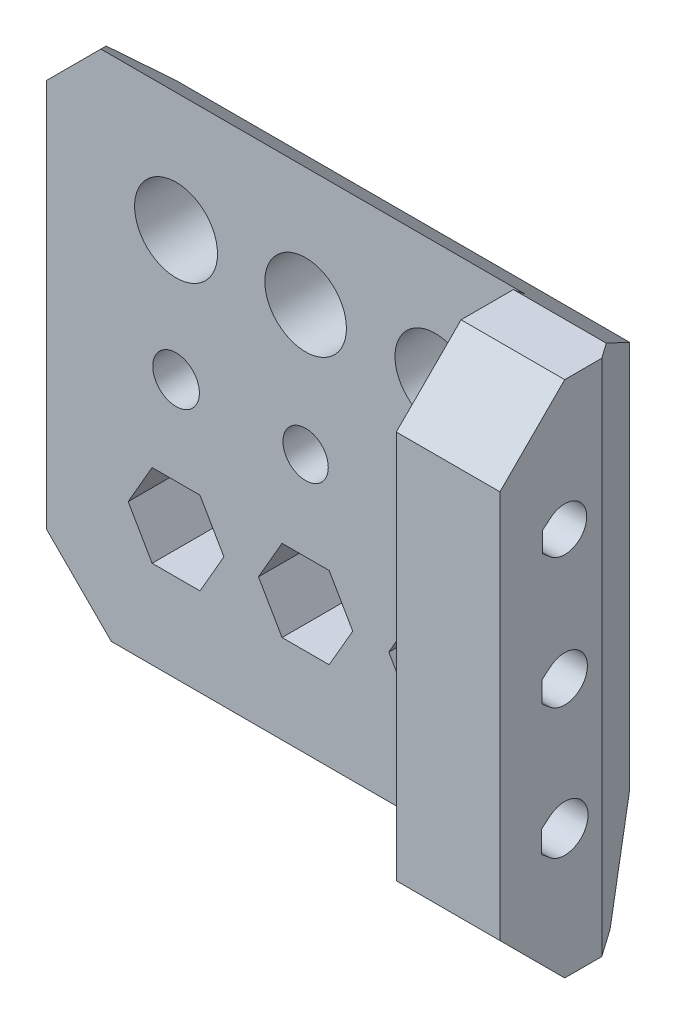
SolidWorks part; units mm, degrees
ref_plane "Front Plane" through (0, 0, 0) normal (0, 0, 1) x (1, 0, 0)
ref_plane "Top Plane" through (0, 0, 0) normal (0, 1, 0) x (1, 0, 0)
ref_plane "Right Plane" through (0, 0, 0) normal (1, 0, 0) x (0, 0, -1)
sketch "Sketch1" plane through (0, 0, 0) normal (0, 0, 1) x (1, 0, 0)
  line L0 (0, 0) -> (-30, 0) construction
  line L1 (-30, -20) -> (15, -20)
  line L2 (-30, -20) -> (-30, 20)
  line L3 (-30, 20) -> (15, 20)
  line L4 (15, -20) -> (15, 20)
  line L5 (-16.305, -10) -> (-18.1525, -6.8)
  line L6 (-18.1525, -6.8) -> (-21.8475, -6.8)
  line L7 (-21.8475, -6.8) -> (-23.695, -10)
  line L8 (-23.695, -10) -> (-21.8475, -13.2)
  line L9 (-21.8475, -13.2) -> (-18.1525, -13.2)
  line L10 (-18.1525, -13.2) -> (-16.305, -10)
  line L11 (-6.3627, -10) -> (-8.1813, -6.85)
  line L12 (-8.1813, -6.85) -> (-11.8187, -6.85)
  line L13 (-11.8187, -6.85) -> (-13.6373, -10)
  line L14 (-13.6373, -10) -> (-11.8187, -13.15)
  line L15 (-11.8187, -13.15) -> (-8.1813, -13.15)
  line L16 (-8.1813, -13.15) -> (-6.3627, -10)
  line L17 (3.5796, -10) -> (1.7898, -6.9)
  line L18 (1.7898, -6.9) -> (-1.7898, -6.9)
  line L19 (-1.7898, -6.9) -> (-3.5796, -10)
  line L20 (-3.5796, -10) -> (-1.7898, -13.1)
  line L21 (-1.7898, -13.1) -> (1.7898, -13.1)
  line L22 (1.7898, -13.1) -> (3.5796, -10)
  circle A0 centre (-20, 0) radius 1.8
  circle A1 centre (-10, 0) radius 1.75
  circle A2 centre (0, 0) radius 1.7
  circle A3 centre (-20, 10) radius 3.2
  circle A4 centre (-10, 10) radius 3.15
  circle A5 centre (0, 10) radius 3.1
  circle A6 centre (-20, -10) radius 3.2 construction
  circle A7 centre (-10, -10) radius 3.15 construction
  circle A8 centre (0, -10) radius 3.1 construction
  dimension "D1" = 6.4
  dimension "D2" = 6.3
  dimension "D3" = 6.2
  dimension "D4" = 3.4
  dimension "D5" = 3.5
  dimension "D6" = 3.6
  dimension "D7" = 6.4
  dimension "D8" = 6.3
  dimension "D9" = 6.2
  dimension "D10" = 10
  dimension "D11" = 10
  dimension "D12" = 10
  dimension "D13" = 10
  dimension "D14" = 10
  dimension "D15" = 15
  dimension "D16" = 10
  dimension "D17" = 10
extrude "Boss-Extrude1" add sketch "Sketch1" along normal blind 5
sketch "Sketch2" plane through (0, 0, 5) normal (0, 0, 1) x (1, 0, 0)
  line L0 (-30, -20) -> (15, -20) construction
  line L1 (15, 20) -> (7, 20)
  line L2 (15, 20) -> (15, -20)
  line L3 (15, -20) -> (7, -20)
  line L4 (7, 20) -> (7, -20)
  dimension "D1" = 8
extrude "Boss-Extrude2" add sketch "Sketch2" along normal blind 10
sketch "Sketch3" plane through (15, 0, 0) normal (1, 0, 0) x (0, 0, -1)
  line L0 (-15, 20) -> (0, 20) construction
  line L1 (-10, 20) -> (-10, -20) construction
  line L2 (-15, -20) -> (0, -20) construction
  line L3 (0, -20) -> (0, 20) construction
  line L4 (-10, 12.2192) -> (-11.7, 10.7927) construction
  line L5 (-11.7, 10.7927) -> (-11.7, 9.2073) construction
  line L6 (-11.7, 9.2073) -> (-10, 7.7808) construction
  line L7 (-10, 2.2845) -> (-11.75, 0.816) construction
  line L8 (-11.75, 0.816) -> (-11.75, -0.816) construction
  line L9 (-11.75, -0.816) -> (-10, -2.2845) construction
  line L10 (-10, -7.6503) -> (-11.8, -9.1606) construction
  line L11 (-11.8, -9.1606) -> (-11.8, -10.8394) construction
  line L12 (-11.8, -10.8394) -> (-10, -12.3497) construction
  line L13 (-11.0927, 11.3023) -> (-11.7, 10.7927)
  line L14 (-11.7, 10.7927) -> (-11.7, 9.2073)
  line L15 (-11.7, 9.2073) -> (-11.0927, 8.6977)
  line L16 (-11.1249, 1.3406) -> (-11.75, 0.816)
  line L17 (-11.75, 0.816) -> (-11.75, -0.816)
  line L18 (-11.75, -0.816) -> (-11.1249, -1.3406)
  line L19 (-11.157, -8.6211) -> (-11.8, -9.1606)
  line L20 (-11.8, -9.1606) -> (-11.8, -10.8394)
  line L21 (-11.8, -10.8394) -> (-11.157, -11.3789)
  arc A0 (-11.0927, 8.6977) -> (-11.0927, 11.3023) centre (-10, 10) ccw
  arc A1 (-11.1249, -1.3406) -> (-11.1249, 1.3406) centre (-10, 0) ccw
  arc A2 (-11.157, -11.3789) -> (-11.157, -8.6211) centre (-10, -10) ccw
  dimension "D1" = 3.4
  dimension "D2" = 3.5
  dimension "D3" = 3.6
  dimension "D4" = 10
  dimension "D5" = 10
  dimension "D6" = 10
  dimension "D7" = 10
  dimension "D8" = 50
  dimension "D9" = 50
  dimension "D10" = 50
extrude "Cut-Extrude1" cut sketch "Sketch3" against normal up to next
chamfer "Chamfer1" distance 5 angle 45 4 edges at (-30, -20, 2.5) (-30, 20, 2.5) (11, -20, 15) (11, 20, 15)
chamfer "Chamfer2" distance 5 angle 50 1 edges at (-5, 20, 0)
chamfer "Chamfer3" distance 5 angle 45 1 edges at (-5, -20, 0)
chamfer "Chamfer4" distance 5 angle 55 1 edges at (15, 0, 0)
chamfer "Chamfer5" distance 5 angle 40 1 edges at (-30, 0, 0)
